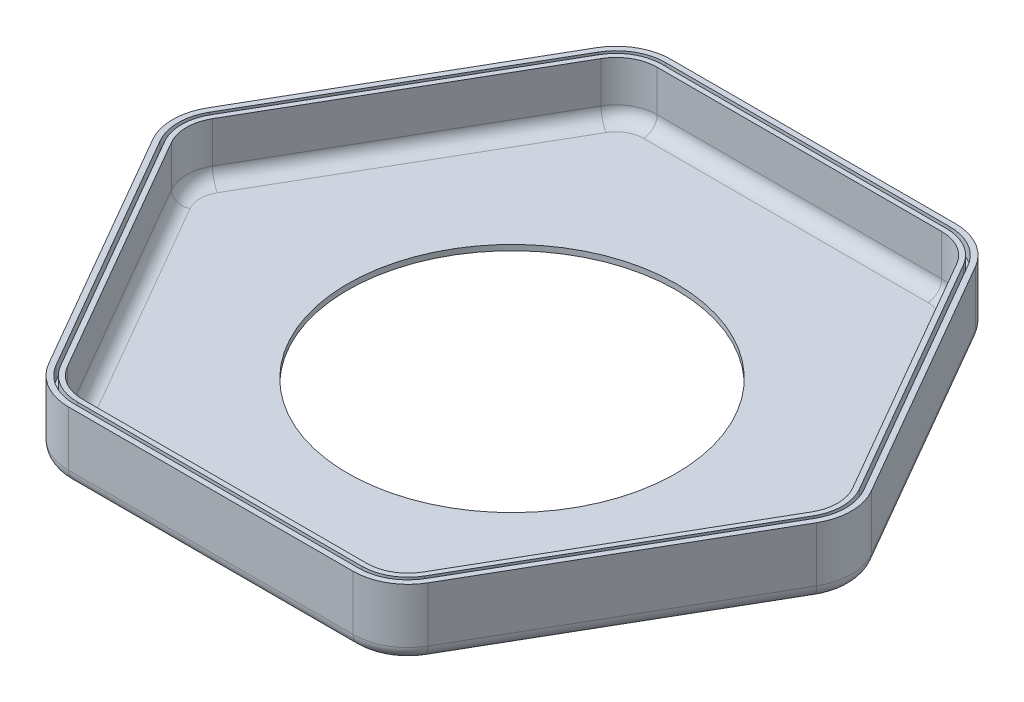
SolidWorks part; units mm, degrees
ref_plane "Front" through (0, 0, 0) normal (0, 0, 1) x (1, 0, 0)
ref_plane "Top" through (0, 0, 0) normal (0, 1, 0) x (1, 0, 0)
ref_plane "Right" through (0, 0, 0) normal (1, 0, 0) x (0, 0, -1)
sketch "Croquis1" plane through (0, 0, 0) normal (0, 1, 0) x (1, 0, 0)
  line L0 (-119.2242, -9.3942) -> (-67.2627, -99.3942)
  line L1 (-49.9422, -109.3942) -> (53.9809, -109.3942)
  line L2 (71.3014, -99.3942) -> (123.2629, -9.3942)
  line L3 (123.2629, 10.6058) -> (71.3014, 100.6058)
  line L4 (53.9809, 110.6058) -> (-49.9422, 110.6058)
  line L5 (-67.2627, 100.6058) -> (-119.2242, 10.6058)
  circle A0 centre (2.0194, 0.6058) radius 110 construction
  arc A1 (-67.2627, 100.6058) -> (-49.9422, 110.6058) centre (-49.9422, 90.6058) cw
  arc A2 (71.3014, 100.6058) -> (53.9809, 110.6058) centre (53.9809, 90.6058) ccw
  arc A3 (123.2629, -9.3942) -> (123.2629, 10.6058) centre (105.9424, 0.6058) ccw
  arc A4 (53.9809, -109.3942) -> (71.3014, -99.3942) centre (53.9809, -89.3942) ccw
  arc A5 (-67.2627, -99.3942) -> (-49.9422, -109.3942) centre (-49.9422, -89.3942) ccw
  arc A6 (-119.2242, -9.3942) -> (-119.2242, 10.6058) centre (-101.9037, 0.6058) cw
  dimension "D1" = 220
  dimension "D2" = 20
extrude "Saliente-Extruir2" add sketch "Croquis1" along normal blind 5
sketch "Croquis2" plane through (0, 5, 0) normal (0, 1, 0) x (1, 0, 0)
  line L6 (-62.9325, 98.1058) -> (-114.8941, 8.1058)
  line L7 (-114.8941, -6.8942) -> (-62.9325, -96.8942)
  line L8 (-49.9422, -104.3942) -> (53.9809, -104.3942)
  line L9 (66.9713, -96.8942) -> (118.9328, -6.8942)
  line L10 (118.9328, 8.1058) -> (66.9713, 98.1058)
  line L11 (53.9809, 105.6058) -> (-49.9422, 105.6058)
  line L12 (-67.2627, 100.6058) -> (-119.2242, 10.6058)
  line L13 (-119.2242, -9.3942) -> (-67.2627, -99.3942)
  line L14 (-49.9422, -109.3942) -> (53.9809, -109.3942)
  line L15 (71.3014, -99.3942) -> (123.2629, -9.3942)
  line L16 (123.2629, 10.6058) -> (71.3014, 100.6058)
  line L17 (53.9809, 110.6058) -> (-49.9422, 110.6058)
  line L18 (-67.2627, 100.6058) -> (-119.2242, 10.6058)
  line L19 (-119.2242, -9.3942) -> (-67.2627, -99.3942)
  line L20 (-49.9422, -109.3942) -> (53.9809, -109.3942)
  line L21 (71.3014, -99.3942) -> (123.2629, -9.3942)
  line L22 (123.2629, 10.6058) -> (71.3014, 100.6058)
  line L23 (53.9809, 110.6058) -> (-49.9422, 110.6058)
  arc A6 (-114.8941, 8.1058) -> (-114.8941, -6.8942) centre (-101.9037, 0.6058) ccw
  arc A7 (-62.9325, -96.8942) -> (-49.9422, -104.3942) centre (-49.9422, -89.3942) ccw
  arc A8 (53.9809, -104.3942) -> (66.9713, -96.8942) centre (53.9809, -89.3942) ccw
  arc A9 (118.9328, -6.8942) -> (118.9328, 8.1058) centre (105.9424, 0.6058) ccw
  arc A10 (66.9713, 98.1058) -> (53.9809, 105.6058) centre (53.9809, 90.6058) ccw
  arc A11 (-49.9422, 105.6058) -> (-62.9325, 98.1058) centre (-49.9422, 90.6058) ccw
  arc A12 (-49.9422, 110.6058) -> (-67.2627, 100.6058) centre (-49.9422, 90.6058) ccw
  arc A13 (-119.2242, 10.6058) -> (-119.2242, -9.3942) centre (-101.9037, 0.6058) ccw
  arc A14 (-67.2627, -99.3942) -> (-49.9422, -109.3942) centre (-49.9422, -89.3942) ccw
  arc A15 (53.9809, -109.3942) -> (71.3014, -99.3942) centre (53.9809, -89.3942) ccw
  arc A16 (123.2629, -9.3942) -> (123.2629, 10.6058) centre (105.9424, 0.6058) ccw
  arc A17 (71.3014, 100.6058) -> (53.9809, 110.6058) centre (53.9809, 90.6058) ccw
  arc A18 (-49.9422, 110.6058) -> (-67.2627, 100.6058) centre (-49.9422, 90.6058) ccw
  arc A19 (-119.2242, 10.6058) -> (-119.2242, -9.3942) centre (-101.9037, 0.6058) ccw
  arc A20 (-67.2627, -99.3942) -> (-49.9422, -109.3942) centre (-49.9422, -89.3942) ccw
  arc A21 (53.9809, -109.3942) -> (71.3014, -99.3942) centre (53.9809, -89.3942) ccw
  arc A22 (123.2629, -9.3942) -> (123.2629, 10.6058) centre (105.9424, 0.6058) ccw
  arc A23 (71.3014, 100.6058) -> (53.9809, 110.6058) centre (53.9809, 90.6058) ccw
  dimension "D1" = 0
  dimension "D2" = 5
extrude "Saliente-Extruir3" add sketch "Croquis2" along normal blind 20
fillet "Redondeo2" radius 5 12 edges at (-93.2434, 0, -55.6058) (-121.9037, 0, -0.6058) (-93.2434, 0, 54.3942) (-59.9422, 0, 106.7147) (2.0194, 0, 109.3942) (63.9809, 0, 106.7147) (97.2822, 0, 54.3942) (125.9424, 0, -0.6058) (97.2822, 0, -55.6058) (63.9809, 0, -107.9263) (2.0194, 0, -110.6058) (-59.9422, 0, -107.9263)
fillet "Redondeo3" radius 5 12 edges at (61.4809, 5, -103.5962) (92.952, 5, -53.1058) (120.9424, 5, -0.6058) (92.952, 5, 51.8942) (61.4809, 5, 102.3846) (2.0194, 5, 104.3942) (-57.4422, 5, 102.3846) (-88.9133, 5, 51.8942) (-116.9037, 5, -0.6058) (-88.9133, 5, -53.1058) (-57.4422, 5, -103.5962) (2.0194, 5, -105.6058)
sketch "Croquis3" plane through (0, 0, 0) normal (0, -1, 0) x (1, 0, 0)
  line L0 (-57.4422, 102.3846) -> (61.4809, -103.5962) construction
  line L1 (-57.4422, -103.5962) -> (61.4809, 102.3846) construction
  arc A0 (-49.9422, 104.3942) -> (-62.9325, 96.8942) centre (-49.9422, 89.3942) ccw construction
  arc A1 (53.9809, -105.6058) -> (66.9713, -98.1058) centre (53.9809, -90.6058) ccw construction
  arc A2 (-62.9325, -98.1058) -> (-49.9422, -105.6058) centre (-49.9422, -90.6058) ccw construction
  arc A3 (66.9713, 96.8942) -> (53.9809, 104.3942) centre (53.9809, 89.3942) ccw construction
  circle A4 centre (2.0194, -0.6058) radius 90
sketch "Croquis4" plane through (0, 0, 0) normal (0, -1, 0) x (-1, 0, 0)
  circle A0 centre (-2.0194, 0.6058) radius 60
extrude "Cortar-Extruir1" cut sketch "Croquis4" against normal blind 10
extrude "Cortar-Extruir2" cut sketch "Croquis3" against normal blind 3
sketch "Croquis5" plane through (0, 25, 0) normal (0, 1, 0) x (1, 0, 0)
  line L12 (-65.5306, 99.6058) -> (-117.4921, 9.6058)
  line L13 (-117.4921, -8.3942) -> (-65.5306, -98.3942)
  line L14 (-49.9422, -107.3942) -> (53.9809, -107.3942)
  line L15 (69.5693, -98.3942) -> (121.5309, -8.3942)
  line L16 (121.5309, 9.6058) -> (69.5693, 99.6058)
  line L17 (53.9809, 108.6058) -> (-49.9422, 108.6058)
  line L18 (-65.5306, 99.6058) -> (-117.4921, 9.6058)
  line L19 (-117.4921, -8.3942) -> (-65.5306, -98.3942)
  line L20 (-49.9422, -107.3942) -> (53.9809, -107.3942)
  line L21 (69.5693, -98.3942) -> (121.5309, -8.3942)
  line L22 (121.5309, 9.6058) -> (69.5693, 99.6058)
  line L23 (53.9809, 108.6058) -> (-49.9422, 108.6058)
  line L30 (-64.4914, 99.0058) -> (-116.4529, 9.0058)
  line L31 (-116.4529, -7.7942) -> (-64.4914, -97.7942)
  line L32 (-49.9422, -106.1942) -> (53.9809, -106.1942)
  line L33 (68.5301, -97.7942) -> (120.4916, -7.7942)
  line L34 (120.4916, 9.0058) -> (68.5301, 99.0058)
  line L35 (53.9809, 107.4058) -> (-49.9422, 107.4058)
  line L36 (-64.4914, 99.0058) -> (-116.4529, 9.0058)
  line L37 (-116.4529, -7.7942) -> (-64.4914, -97.7942)
  line L38 (-49.9422, -106.1942) -> (53.9809, -106.1942)
  line L39 (68.5301, -97.7942) -> (120.4916, -7.7942)
  line L40 (120.4916, 9.0058) -> (68.5301, 99.0058)
  line L41 (53.9809, 107.4058) -> (-49.9422, 107.4058)
  arc A12 (-49.9422, 108.6058) -> (-65.5306, 99.6058) centre (-49.9422, 90.6058) ccw
  arc A13 (-117.4921, 9.6058) -> (-117.4921, -8.3942) centre (-101.9037, 0.6058) ccw
  arc A14 (-65.5306, -98.3942) -> (-49.9422, -107.3942) centre (-49.9422, -89.3942) ccw
  arc A15 (53.9809, -107.3942) -> (69.5693, -98.3942) centre (53.9809, -89.3942) ccw
  arc A16 (121.5309, -8.3942) -> (121.5309, 9.6058) centre (105.9424, 0.6058) ccw
  arc A17 (69.5693, 99.6058) -> (53.9809, 108.6058) centre (53.9809, 90.6058) ccw
  arc A18 (-49.9422, 108.6058) -> (-65.5306, 99.6058) centre (-49.9422, 90.6058) ccw
  arc A19 (-117.4921, 9.6058) -> (-117.4921, -8.3942) centre (-101.9037, 0.6058) ccw
  arc A20 (-65.5306, -98.3942) -> (-49.9422, -107.3942) centre (-49.9422, -89.3942) ccw
  arc A21 (53.9809, -107.3942) -> (69.5693, -98.3942) centre (53.9809, -89.3942) ccw
  arc A22 (121.5309, -8.3942) -> (121.5309, 9.6058) centre (105.9424, 0.6058) ccw
  arc A23 (69.5693, 99.6058) -> (53.9809, 108.6058) centre (53.9809, 90.6058) ccw
  arc A30 (-49.9422, 107.4058) -> (-64.4914, 99.0058) centre (-49.9422, 90.6058) ccw
  arc A31 (-116.4529, 9.0058) -> (-116.4529, -7.7942) centre (-101.9037, 0.6058) ccw
  arc A32 (-64.4914, -97.7942) -> (-49.9422, -106.1942) centre (-49.9422, -89.3942) ccw
  arc A33 (53.9809, -106.1942) -> (68.5301, -97.7942) centre (53.9809, -89.3942) ccw
  arc A34 (120.4916, -7.7942) -> (120.4916, 9.0058) centre (105.9424, 0.6058) ccw
  arc A35 (68.5301, 99.0058) -> (53.9809, 107.4058) centre (53.9809, 90.6058) ccw
  arc A36 (-49.9422, 107.4058) -> (-64.4914, 99.0058) centre (-49.9422, 90.6058) ccw
  arc A37 (-116.4529, 9.0058) -> (-116.4529, -7.7942) centre (-101.9037, 0.6058) ccw
  arc A38 (-64.4914, -97.7942) -> (-49.9422, -106.1942) centre (-49.9422, -89.3942) ccw
  arc A39 (53.9809, -106.1942) -> (68.5301, -97.7942) centre (53.9809, -89.3942) ccw
  arc A40 (120.4916, -7.7942) -> (120.4916, 9.0058) centre (105.9424, 0.6058) ccw
  arc A41 (68.5301, 99.0058) -> (53.9809, 107.4058) centre (53.9809, 90.6058) ccw
  dimension "D1" = 2
  dimension "D2" = 3.2
extrude "Cortar-Extruir3" cut sketch "Croquis5" against normal blind 5
